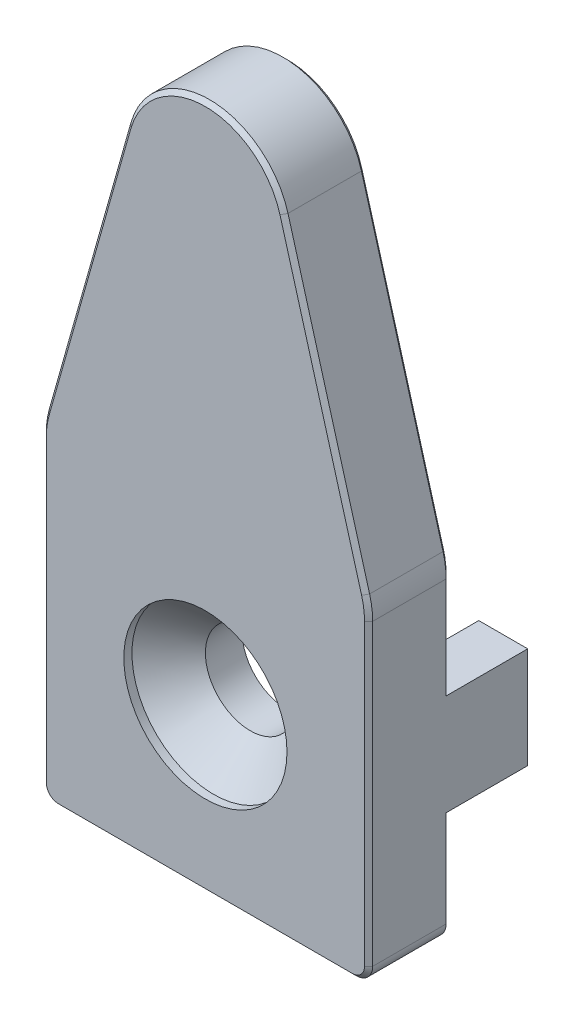
SolidWorks part; units mm, degrees
ref_plane "Front Plane" through (0, 0, 0) normal (0, 0, 1) x (1, 0, 0)
ref_plane "Top Plane" through (0, 0, 0) normal (0, 1, 0) x (1, 0, 0)
ref_plane "Right Plane" through (0, 0, 0) normal (1, 0, 0) x (0, 0, -1)
sketch "Sketch1" plane through (0, 0, 0) normal (0, 0, 1) x (1, 0, 0)
  line L0 (-21.8994, 0) -> (21.4746, 0) construction
  line L1 (0, 20.9985) -> (0, -16.0644) construction
  line L2 (-10, 10) -> (10, 10) construction
  line L3 (-10, 44) -> (10, 44)
  line L4 (-10, 44) -> (-10, -10)
  line L5 (-10, -10) -> (10, -10)
  line L6 (10, 44) -> (10, -10)
  line L7 (-10, 44) -> (10, -10) construction
  line L8 (-10, -10) -> (10, 44) construction
  line L9 (-10, 10) -> (10, -10) construction
  line L10 (-10, 10) -> (-10, -10) construction
  line L11 (-10, 10) -> (10, 44) construction
  line L12 (-10, 10) -> (-4.8116, 28.3597)
  line L13 (10, 10) -> (4.8116, 28.3597)
  circle A0 centre (0, 27) radius 5
  circle A1 centre (0, 0) radius 2.75
  point P4 (0, 17)
  point P12 (0, 0)
  point P13 (0, 27)
  dimension "D3" = 10
  dimension "D4" = 5.5
  dimension "D1" = 20
  dimension "D2" = 34
extrude "Boss-Extrude1" add sketch "Sketch1" along normal blind 5 contours A0 | A0 L12 L4 L5 L6 L13 A1
sketch "Sketch2" plane through (0, 0, 0) normal (0, 0, -1) x (-1, 0, 0)
  line L0 (-13.211, 0) -> (15.4195, 0) construction
  line L1 (0, 13.8394) -> (0, -6.1152) construction
  line L2 (-10, 10) -> (-10, -10) construction
  line L3 (-7, -3.1) -> (-10, -3.1)
  line L4 (-7, -3.1) -> (-7, 3.1)
  line L5 (-7, 3.1) -> (-10, 3.1)
  line L6 (-10, -3.1) -> (-10, 3.1)
  line L7 (-7, -3.1) -> (-10, 3.1) construction
  line L8 (-7, 3.1) -> (-10, -3.1) construction
  line L9 (7, -3.1) -> (10, -3.1)
  line L10 (10, -3.1) -> (10, 3.1)
  line L11 (7, 3.1) -> (10, 3.1)
  line L12 (7, -3.1) -> (7, 3.1)
  point P4 (-8.5, 0)
  dimension "D1" = 6.2
  dimension "D2" = 3
extrude "Boss-Extrude2" add sketch "Sketch2" along normal blind 5
fillet "Fillet1" radius 1 4 edges at (10, -10, 2.5) (-10, -10, 2.5) (-7, 0, 0) (7, 0, 0)
fillet "Fillet2" radius 5 2 edges at (10, 10, 2.5) (-10, 10, 2.5)
hole_wizard "CSK for M5 Flat Head Machine Screw1" positions "Sketch3" profile "Sketch4" countersink size "M5" standard "ANSI Metric" end condition through all
sketch "Sketch3" plane through (0, 0, 5) normal (0, 0, 1) x (1, 0, 0)
  point P0 (0, 0)
sketch "Sketch4" plane through (0, 0, 5) normal (1, 0, 0) x (0, -1, 0)
  line L0 (0, 0) -> (0, 10)
  line L1 (0, 10) -> (2.75, 10)
  line L2 (2.75, 10) -> (2.75, 2.75)
  line L3 (2.75, 2.75) -> (5, 0.5)
  line L4 (5, 0.5) -> (5, 0)
  line L6 (5, 0) -> (0, 0)
  line L7 (-2.75, 2.75) -> (-5, 0.5) construction
  line L11 (0, -6.35) -> (0, 107.95) construction
  dimension "Thru Hole Dia." = 5.5
  dimension "Thru Hole Depth" = 10
  dimension "C'Sink Dia." = 10
  dimension "C'Sink Angle" = 90
  dimension "Head Clearance" = 0.5
chamfer "Chamfer1" distance 0.25 angle 45 30 edges at (10, -6.05, 0) (9.7071, -9.7071, 5) (9.7071, -9.7071, 0) (0, -10, 0) (0, -10, 5) (-9.7071, -9.7071, 5) (-9.7071, -9.7071, 0) (-10, -6.05, 0) (10, 6.2035, 0) (9.9527, 9.9934, 5) (9.9527, 9.9934, 0) (-10, 6.2035, 0) (7.3116, 19.5133, 5) (7.3116, 19.5133, 0) (-9.9527, 9.9934, 5) (-9.9527, 9.9934, 0) (0, 32, 0) (0, 32, 5) (-7.3116, 19.5133, 0) (-7.3116, 19.5133, 5) (-10, 0.1535, 5) (10, 0.1535, 5) (-8.5, 3.1, -5) (-10, 0, -5) (-8.5, -3.1, -5) (-7, 0, -5) (8.5, 3.1, -5) (7, 0, -5) (8.5, -3.1, -5) (10, 0, -5)
